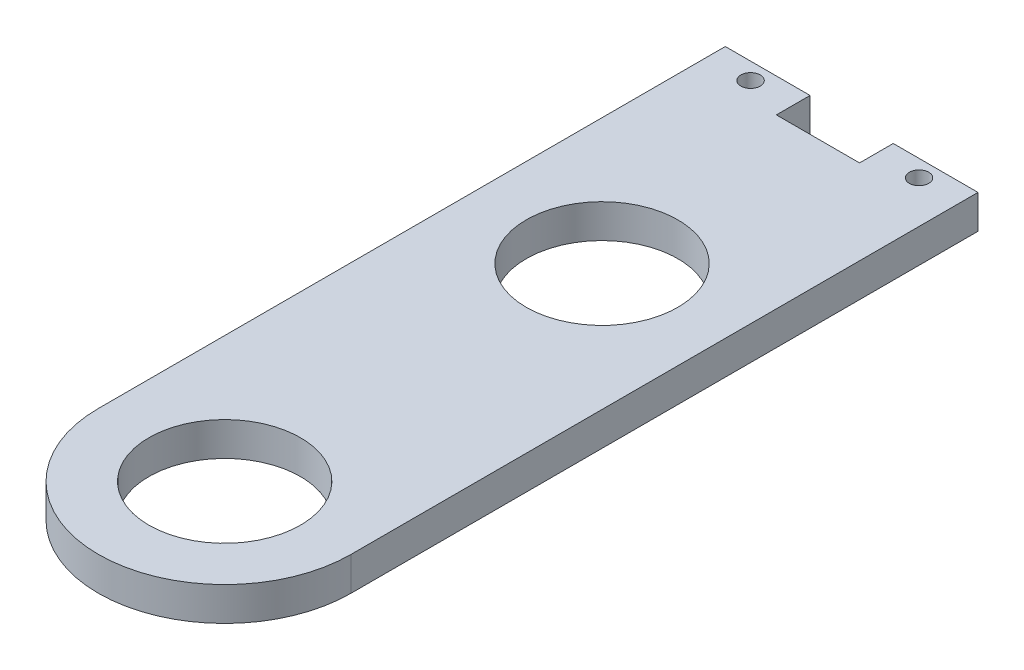
SolidWorks part; units mm, degrees
ref_plane "Front Plane" through (0, 0, 0) normal (0, 0, 1) x (1, 0, 0)
ref_plane "Top Plane" through (0, 0, 0) normal (0, 1, 0) x (1, 0, 0)
ref_plane "Right Plane" through (0, 0, 0) normal (1, 0, 0) x (0, 0, -1)
sketch "Sketch1" plane through (0, 0, 0) normal (0, 1, 0) x (1, 0, 0)
  line L0 (-23.8125, 67.2592) -> (23.8125, 67.2592) construction
  line L1 (-23.8125, -76.2) -> (23.8125, -76.2)
  line L2 (-23.8125, -76.2) -> (-23.8125, 76.2)
  line L3 (-23.8125, 76.2) -> (23.8125, 76.2)
  line L4 (23.8125, -76.2) -> (23.8125, 76.2)
  line L5 (-23.8125, -76.2) -> (23.8125, 76.2) construction
  line L6 (-23.8125, 76.2) -> (23.8125, -76.2) construction
  line L8 (7.3323, -35.6108) -> (3.6662, -29.2608)
  line L9 (3.6662, -29.2608) -> (-3.6662, -29.2608)
  line L10 (-3.6662, -29.2608) -> (-7.3323, -35.6108)
  line L11 (-7.3323, -35.6108) -> (-3.6662, -41.9608)
  line L12 (-3.6662, -41.9608) -> (3.6662, -41.9608)
  line L13 (3.6662, -41.9608) -> (7.3323, -35.6108)
  line L14 (5.4993, 35.5092) -> (2.7496, 40.2717)
  line L15 (2.7496, 40.2717) -> (-2.7496, 40.2717)
  line L16 (-2.7496, 40.2717) -> (-5.4993, 35.5092)
  line L17 (-5.4993, 35.5092) -> (-2.7496, 30.7467)
  line L18 (-2.7496, 30.7467) -> (2.7496, 30.7467)
  line L19 (2.7496, 30.7467) -> (5.4993, 35.5092)
  circle A0 centre (0, 35.5092) radius 14.2875
  circle A1 centre (0, 35.5092) radius 4.7625 construction
  circle A2 centre (0, -35.6108) radius 14.2875
  circle A3 centre (0, -35.6108) radius 6.35 construction
  circle A4 centre (0, 35.5092) radius 31.75
  circle A5 centre (0, -35.6108) radius 53.34
  point P0 (0, 0)
  dimension "D3" = 28.575
  dimension "D4" = 9.525
  dimension "D5" = 28.575
  dimension "D7" = 12.7
  dimension "D9" = 63.5
  dimension "D10" = 106.68
  dimension "D1" = 47.625
  dimension "D2" = 8.9408
  dimension "D6" = 71.12
  dimension "D8" = 152.4
  dimension "D11" = 31.75
extrude "Boss-Extrude1" add sketch "Sketch1" along normal blind 6.35 contours A4 A0 | L4 A5 L2 L1 A2 | A5 L4 L3 L2 A4 | A5 L4 A4 | A5 A4 L2 | A4 A5
sketch "Sketch2" plane through (0, 6.35, 0) normal (0, 1, 0) x (1, 0, 0)
  line L0 (-23.8125, 76.2) -> (23.8125, 76.2)
  line L1 (23.8125, 76.2) -> (23.8125, 38.1)
  line L2 (23.8125, -76.2) -> (23.8125, 76.2) construction
  line L3 (23.8125, 38.1) -> (23.8125, -35.6108)
  line L4 (-23.8125, 76.2) -> (-23.8125, 38.1)
  line L5 (-23.8125, -76.2) -> (-23.8125, 76.2) construction
  line L6 (-23.8125, 38.1) -> (-23.8125, -35.6108)
  line L7 (-17.4625, 19.3198) -> (-17.4625, -19.4214)
  line L8 (17.4625, 19.3198) -> (17.4625, -19.4214)
  line L9 (-17.4625, 51.6986) -> (-17.4625, 69.85)
  line L10 (-17.4625, 69.85) -> (17.4625, 69.85)
  line L11 (0, 35.5092) -> (0, -35.6108) construction
  line L12 (3.175, 11.9093) -> (3.175, -12.0109)
  line L13 (-3.175, 11.9093) -> (-3.175, -12.0109)
  line L14 (17.4625, 69.85) -> (17.4625, 51.6986)
  line L15 (0, 35.5092) -> (0, 69.85) construction
  line L16 (-3.175, 59.1091) -> (-3.175, 69.85)
  line L17 (3.175, 59.1091) -> (3.175, 69.85)
  circle A0 centre (0, 35.5092) radius 23.8125
  circle A1 centre (0, -35.6108) radius 23.8125
  line M2 (-23.8125, 76.2) -> (-23.8125, -76.2)
  line M3 (-23.8125, -76.2) -> (23.8125, -76.2)
  line M4 (23.8125, -76.2) -> (23.8125, 76.2)
  dimension "D1" = 47.625
  dimension "D2" = 47.625
  dimension "D3" = 6.35
  dimension "D4" = 6.35
  dimension "D5" = 6.35
  dimension "D6" = 6.35
  dimension "D7" = 6.35
  dimension "D8" = 6.35
extrude "Cut-Extrude1" cut sketch "Sketch2" against normal through all contours A1 L6 L3 M2 M3 M4
sketch "Sketch3" plane through (0, 6.35, 0) normal (0, 1, 0) x (1, 0, 0)
  line L0 (-23.8125, 76.2) -> (-23.8125, 82.55)
  line L1 (-23.8125, 82.55) -> (-7.8375, 82.55)
  line L2 (-7.8375, 82.55) -> (-7.8375, 76.2)
  line L3 (-23.8125, 76.2) -> (23.8125, 76.2) construction
  line L4 (-7.8375, 76.2) -> (7.8375, 76.2)
  line L5 (7.8375, 76.2) -> (7.8375, 82.55)
  line L6 (7.8375, 82.55) -> (23.8125, 82.55)
  line L7 (23.8125, 82.55) -> (23.8125, 76.2)
  line L8 (-23.8125, 76.2) -> (23.8125, 76.2)
  line L9 (23.8125, -35.6108) -> (23.8125, 76.2) construction
  line M9 (23.8125, 76.2) -> (-23.8125, 76.2)
  dimension "D2" = 15.675
  dimension "D4" = 6.35
extrude "Boss-Extrude2" add sketch "Sketch3" against normal blind 6.35 contours L2 L1 L0 M9 | L7 L6 L5 M9
sketch "Sketch4" plane through (0, 6.35, 0) normal (0, 1, 0) x (1, 0, 0)
  line L2 (-7.8375, 82.55) -> (-7.8375, 76.2) construction
  line L3 (7.8375, 76.2) -> (7.8375, 82.55) construction
  line L4 (-23.8125, 79.375) -> (-7.9375, 79.375) construction
  line L5 (-23.8125, -35.6108) -> (-23.8125, 82.55) construction
  line L6 (23.8125, 79.375) -> (7.9375, 79.375) construction
  line L7 (23.8125, -35.6108) -> (23.8125, 82.55) construction
  circle A0 centre (-15.875, 79.375) radius 1.8288
  circle A1 centre (15.875, 79.375) radius 1.8288
  point P12 (-7.8375, 79.375)
  point P15 (7.8375, 79.375)
  point P24 (-15.875, 79.375)
  point P25 (15.875, 79.375)
  dimension "D1" = 3.6576
  dimension "D2" = 3.6576
  dimension "D3" = 15.875
  dimension "D4" = 15.875
extrude "Cut-Extrude2" cut sketch "Sketch4" against normal through all
